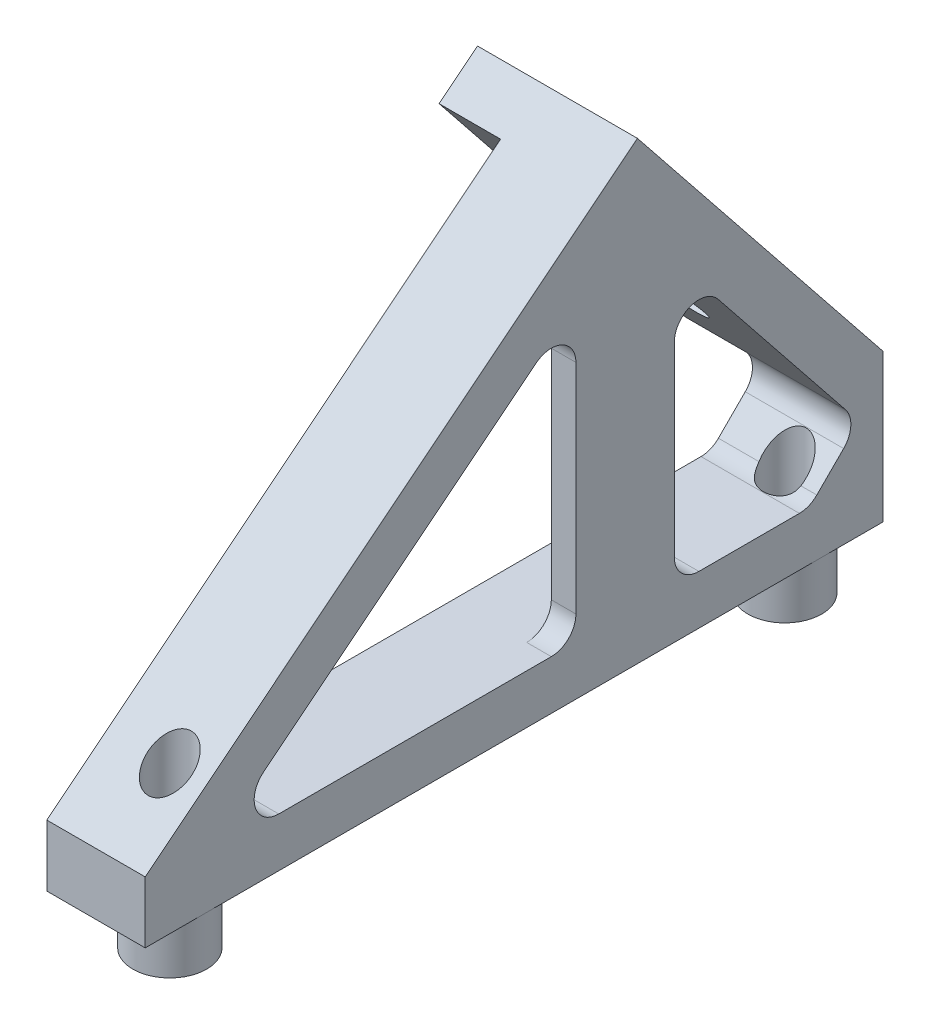
SolidWorks part; units mm, degrees
ref_plane "前基準面" through (0, 0, 0) normal (0, 0, 1) x (1, 0, 0)
ref_plane "上基準面" through (0, 0, 0) normal (0, 1, 0) x (1, 0, 0)
ref_plane "右基準面" through (0, 0, 0) normal (1, 0, 0) x (0, 0, -1)
sketch "草圖4" plane through (0, 0, 0) normal (1, 0, 0) x (0, 0, -1)
  line L0 (0, 0) -> (-60, 0)
  line L1 (-60, 0) -> (-60, 5)
  line L2 (-60, 5) -> (-19.9826, 36.9939)
  line L3 (-19.9826, 36.9939) -> (0, 12)
  line L4 (0, 12) -> (0, 0)
  dimension "D1" = 90
  dimension "D2" = 5
  dimension "D3" = 12
  dimension "D4" = 60
  dimension "D5" = 32
extrude "填料-伸長1" add sketch "草圖4" along normal blind 13
sketch "草圖5" plane through (0, 32.3145, 25.8355) normal (0, 0.7811, 0.6245) x (1, 0, 0)
  line L0 (0, 3.4935) -> (5, 3.4935)
  line L1 (0, 7.4935) -> (0, -43.7413) construction
  line L2 (5, 3.4935) -> (5, -49.0452)
  line L3 (5, -49.0452) -> (0, -49.0452)
  line L4 (0, -49.0452) -> (0, 3.4935)
  line L5 (13, 7.4935) -> (0, 7.4935) construction
  dimension "D1" = 5
  dimension "D2" = 4
extrude "除料-伸長1" cut sketch "草圖5" against normal through all
sketch "草圖6" plane through (13, 0, 0) normal (1, 0, 0) x (0, 0, -1)
  line L0 (-24.9826, 27.8751) -> (-24.9826, 4)
  line L1 (-24.9826, 4) -> (-54.8452, 4)
  line L2 (-54.8452, 4) -> (-24.9826, 27.8751)
  line L3 (-19.9826, 36.9939) -> (-60, 5) construction
  line L4 (-60, 0) -> (0, 0) construction
  line L5 (-16.9826, 26.836) -> (-1.9496, 8.033)
  line L6 (-1.9496, 8.033) -> (-5.9826, 4)
  line L7 (-5.9826, 4) -> (-16.9826, 4)
  line L8 (-16.9826, 4) -> (-16.9826, 26.836)
  line L9 (0, 12) -> (-19.9826, 36.9939) construction
  dimension "D1" = 8
  dimension "D2" = 4
  dimension "D3" = 4
  dimension "D4" = 4
  dimension "D5" = 3
  dimension "D6" = 11
  dimension "D7" = 135
extrude "除料-伸長2" cut sketch "草圖6" against normal through all
fillet "圓角1" radius 2 7 edges at (9, 4, 16.9826) (9, 4, 5.9826) (9, 8.033, 1.9496) (9, 26.836, 16.9826) (9, 4, 54.8452) (9, 4, 24.9826) (9, 27.8751, 24.9826)
sketch "草圖7" plane through (0, 2.1815, -2.7286) normal (0, -0.6245, 0.7811) x (1, 0, 0)
  line L1 (0, 9.3727) -> (5, 9.3727)
  line L2 (5, 4.3696) -> (5, 9.2812) construction
  line L3 (5, 9.3727) -> (5, 4.3696)
  line L4 (5, 4.3696) -> (0, 4.3696)
  line L5 (0, 4.3696) -> (0, 9.3727) construction
  line L6 (0, 4.3696) -> (0, 9.3727)
extrude "除料-伸長3" cut sketch "草圖7" against normal blind 13
sketch "草圖8" plane through (0, 4.6794, -5.8529) normal (0, 0.6245, -0.7811) x (-1, 0, 0)
  line L0 (-13, 41.3727) -> (0, 41.3727) construction
  line L1 (0, 9.3727) -> (0, 41.3727) construction
  line L2 (-5, 9.3727) -> (0, 9.3727) construction
  circle A0 centre (-4, 34.3727) radius 2
  circle A1 centre (-4, 16.3727) radius 2
  dimension "D3" = 4
  dimension "D4" = 4
  dimension "D5" = 4
  dimension "D6" = 7
  dimension "D1" = 7
  dimension "D2" = 4
extrude "除料-伸長4" cut sketch "草圖8" against normal blind 13
sketch "草圖9" plane through (5, 0, 0) normal (-1, 0, 0) x (0, 0, 1)
  line L0 (23.1069, 34.4961) -> (3.1242, 9.5022) construction
  line L1 (20.609, 31.3718) -> (3.0671, 9.4307)
  line L2 (28.2315, 25.2776) -> (50.3898, 7.5621) construction
  line L3 (20.609, 31.3718) -> (50.3898, 7.5621)
  line L4 (5.3968, 4.5858) -> (3.215, 6.7676) construction
  line L5 (5.3968, 4.5858) -> (3.215, 6.7676)
  line L6 (6.811, 4) -> (49.1409, 4)
  arc A0 (3.0671, 9.4307) -> (3.215, 6.7676) centre (4.6292, 8.1818) ccw construction
  arc A1 (5.3968, 4.5858) -> (6.811, 4) centre (6.811, 6) ccw construction
  arc A2 (49.1409, 4) -> (50.3898, 7.5621) centre (49.1409, 6) ccw construction
  arc A3 (3.0671, 9.4307) -> (3.215, 6.7676) centre (4.6292, 8.1818) ccw
  arc A4 (5.3968, 4.5858) -> (6.811, 4) centre (6.811, 6) ccw
  arc A5 (49.1409, 4) -> (50.3898, 7.5621) centre (49.1409, 6) ccw
extrude "除料-伸長5" cut sketch "草圖9" against normal blind 6
sketch "草圖10" plane through (0, 0, 0) normal (0, -1, 0) x (1, 0, 0)
  line L0 (13, 60) -> (13, 0) construction
  line L1 (13, 60) -> (5, 60) construction
  line L2 (13, 0) -> (5, 0) construction
  circle A0 centre (10, 55) radius 3
  circle A1 centre (10, 5) radius 3
  dimension "D1" = 6
  dimension "D2" = 6
  dimension "D3" = 5
  dimension "D4" = 5
extrude "填料-伸長2" add sketch "草圖10" along normal blind 4
sketch "草圖11" plane through (0, -4, 0) normal (0, -1, 0) x (-1, 0, 0)
  circle A0 centre (-10, -55) radius 1.75
  circle A1 centre (-10, -5) radius 1.75
  dimension "D1" = 3.5
extrude "除料-伸長6" cut sketch "草圖11" against normal up to next
